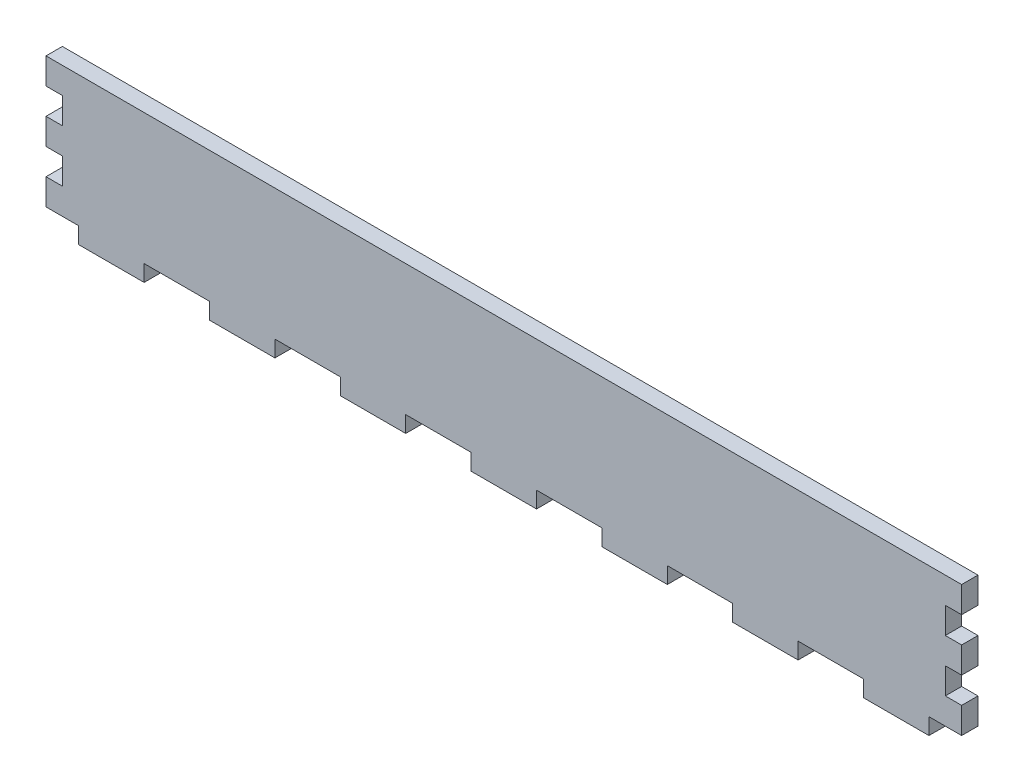
SolidWorks part; units mm, degrees
material "Pin"
ref_plane "Front" through (0, 0, 0) normal (0, 0, 1) x (1, 0, 0)
ref_plane "Top" through (0, 0, 0) normal (0, 1, 0) x (1, 0, 0)
ref_plane "Right" through (0, 0, 0) normal (1, 0, 0) x (0, 0, -1)
sketch "Esquisse1" plane through (0, 0, 0) normal (0, 0, 1) x (1, 0, 0)
  line L1 (-177.8, 25.4) -> (177.8, 25.4)
  line L2 (-177.8, 25.4) -> (-177.8, -25.4)
  line L3 (-177.8, -25.4) -> (177.8, -25.4)
  line L4 (177.8, 25.4) -> (177.8, -25.4)
  line L5 (-177.8, 25.4) -> (177.8, -25.4) construction
  line L6 (-177.8, -25.4) -> (177.8, 25.4) construction
  point P0 (0, 0)
  dimension "D1" = 355.6
  dimension "D2" = 50.8
extrude "Boss.-Extru.1" add sketch "Esquisse1" along normal blind 6.35
sketch "Esquisse2" plane through (0, 0, 6.35) normal (0, 0, 1) x (1, 0, 0)
  line L0 (-177.8, 25.4) -> (-177.8, -25.4) construction
  line L1 (-177.8, -15.24) -> (-171.45, -15.24)
  line L2 (-177.8, -15.24) -> (-177.8, -5.08)
  line L3 (-177.8, -5.08) -> (-171.45, -5.08)
  line L4 (-171.45, -15.24) -> (-171.45, -5.08)
  line L5 (-177.8, -25.4) -> (177.8, -25.4) construction
  dimension "D1" = 6.35
  dimension "D2" = 10.16
  dimension "D3" = 10.16
extrude "Enlèv. mat.-Extru.1" cut sketch "Esquisse2" against normal through all
pattern_linear "Répétition linéaire1" count 2 spacing 20.32 along (0, 1, 0) count 2 spacing 349.25 along (1, 0, 0) of "Enlèv. mat.-Extru.1"
sketch "Esquisse3" plane through (0, 0, 6.35) normal (0, 0, 1) x (1, 0, 0)
  line L0 (-177.8, -25.4) -> (177.8, -25.4) construction
  line L1 (-165.1, -25.4) -> (-139.7, -25.4)
  line L2 (-165.1, -25.4) -> (-165.1, -31.75)
  line L3 (-165.1, -31.75) -> (-139.7, -31.75)
  line L4 (-139.7, -25.4) -> (-139.7, -31.75)
  line L5 (-177.8, -15.24) -> (-177.8, -25.4) construction
  dimension "D1" = 25.4
  dimension "D2" = 6.35
  dimension "D3" = 12.7
extrude "Boss.-Extru.2" add sketch "Esquisse3" against normal blind 6.35
pattern_linear "Répétition linéaire2" count 7 spacing 50.8 along (1, 0, 0) of "Boss.-Extru.2"
sketch "Esquisse4" plane through (0, 0, 6.35) normal (0, 0, 1) x (1, 0, 0)
  line L1 (12.7, -25.4) -> (38.1, -25.4) construction
  text T0 "<b>1</b>" font "Britannic Bold" height 19.05
  text T1 "2" font "Britannic Bold" height 19.05
  text T2 "<b>3</b>" font "Century Gothic" height 19.05
  point P1 (0, -8.087)
  point P3 (0, 0)
  point P6 (0, 0)
  point P7 (0, 0)
  dimension "D1" = 19.05
  dimension "D2" = 6.35
  dimension "D3" = 114.3
  dimension "D4" = 114.3
